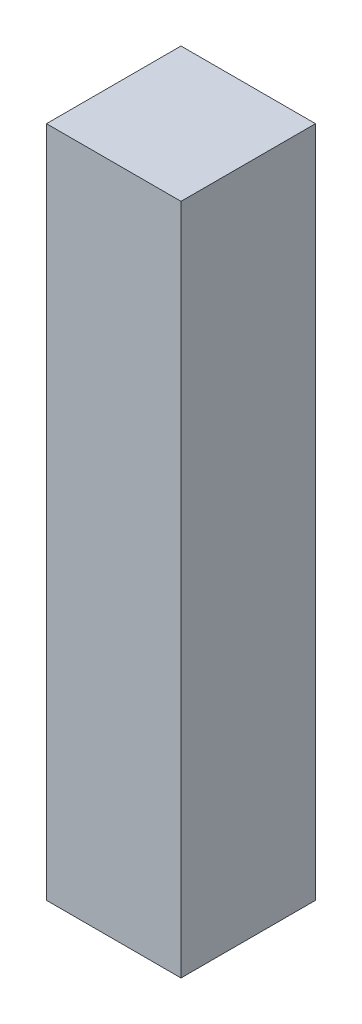
SolidWorks part; units mm, degrees
ref_plane "Front Plane" through (0, 0, 0) normal (0, 0, 1) x (1, 0, 0)
ref_plane "Top Plane" through (0, 0, 0) normal (0, 1, 0) x (1, 0, 0)
ref_plane "Right Plane" through (0, 0, 0) normal (1, 0, 0) x (0, 0, -1)
sketch "Sketch1" plane through (0, 0, 0) normal (0, 1, 0) x (1, 0, 0)
  line L1 (0, 0) -> (20, 0)
  line L2 (0, 0) -> (0, -20)
  line L3 (0, -20) -> (20, -20)
  line L4 (20, 0) -> (20, -20)
extrude "Boss-Extrude1" add sketch "Sketch1" along normal blind 100
